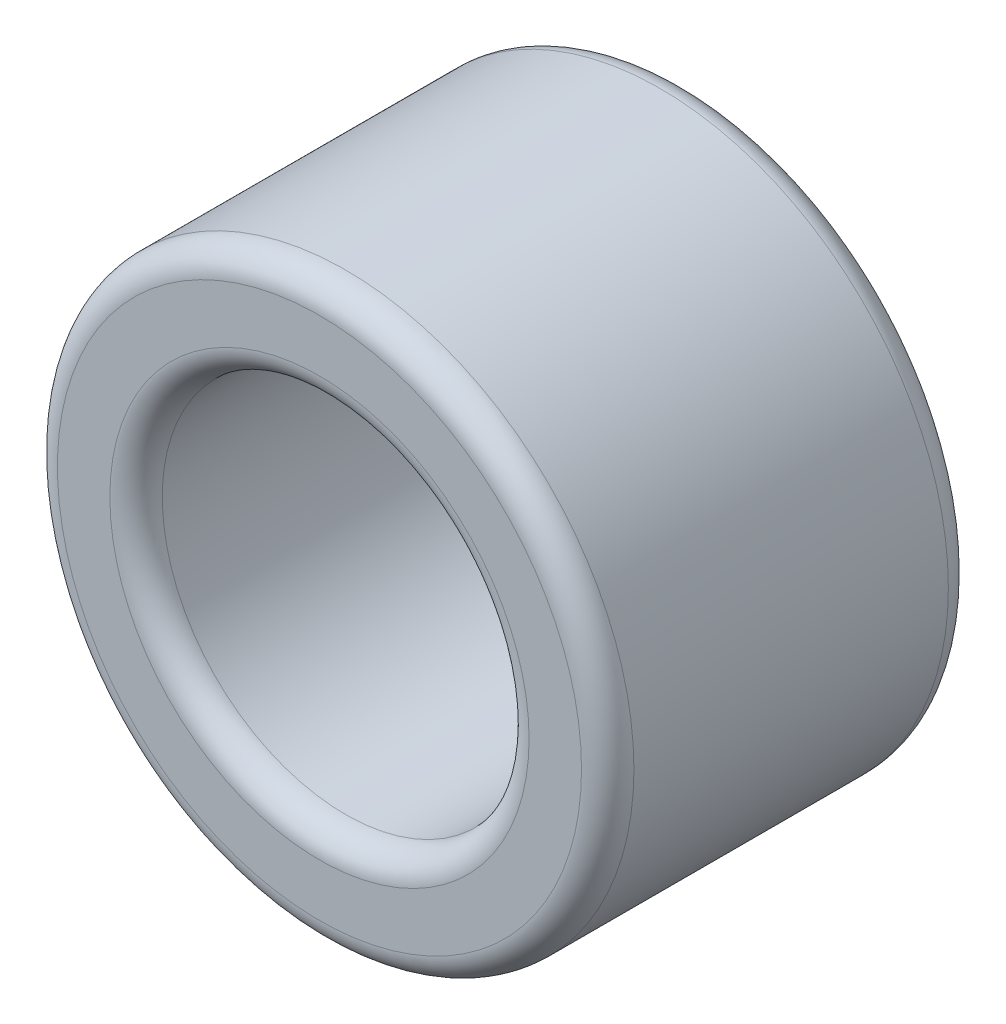
SolidWorks part; units mm, degrees
material "Silicon Rubber"
ref_plane "Front Plane" through (0, 0, 0) normal (0, 0, 1) x (1, 0, 0)
ref_plane "Top Plane" through (0, 0, 0) normal (0, 1, 0) x (1, 0, 0)
ref_plane "Right Plane" through (0, 0, 0) normal (1, 0, 0) x (0, 0, -1)
sketch "Sketch2" plane through (0, 0, 0) normal (0, 0, 1) x (1, 0, 0)
  circle A0 centre (0, 0) radius 279.4
  dimension "D1" = 558.8
extrude "Boss-Extrude1" add sketch "Sketch2" along normal blind 355.6
sketch "Sketch3" plane through (0, 0, 355.6) normal (0, 0, 1) x (1, 0, 0)
  circle A0 centre (0, 0) radius 177.8
  dimension "D1" = 355.6
extrude "Cut-Extrude1" cut sketch "Sketch3" against normal through all
fillet "Fillet3" radius 25.4 2 edges at (279.4, 0, 0) (279.4, 0, 355.6)
fillet "Fillet4" radius 25.4 2 edges at (177.8, 0, 0) (177.8, 0, 355.6)
